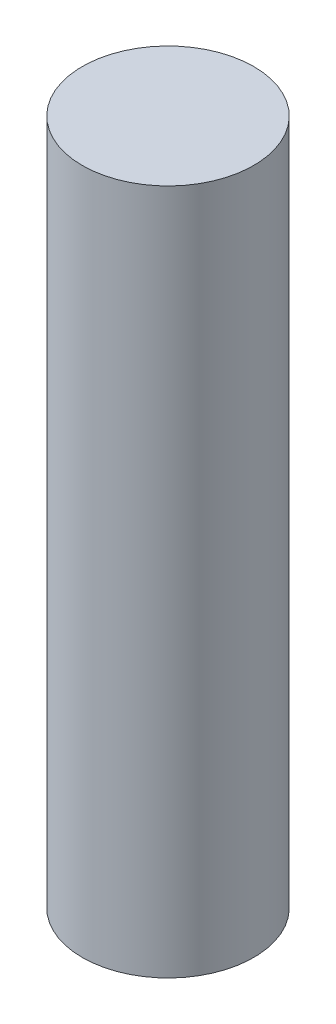
SolidWorks part; units mm, degrees
ref_plane "Front Plane" through (0, 0, 0) normal (0, 0, 1) x (1, 0, 0)
ref_plane "Top Plane" through (0, 0, 0) normal (0, 1, 0) x (1, 0, 0)
ref_plane "Right Plane" through (0, 0, 0) normal (1, 0, 0) x (0, 0, -1)
sketch "Sketch2" plane through (0, 0, 0) normal (0, 1, 0) x (1, 0, 0)
  circle A0 centre (0, 0) radius 6.35
extrude "Boss-Extrude1" add sketch "Sketch2" along normal blind 50.8
